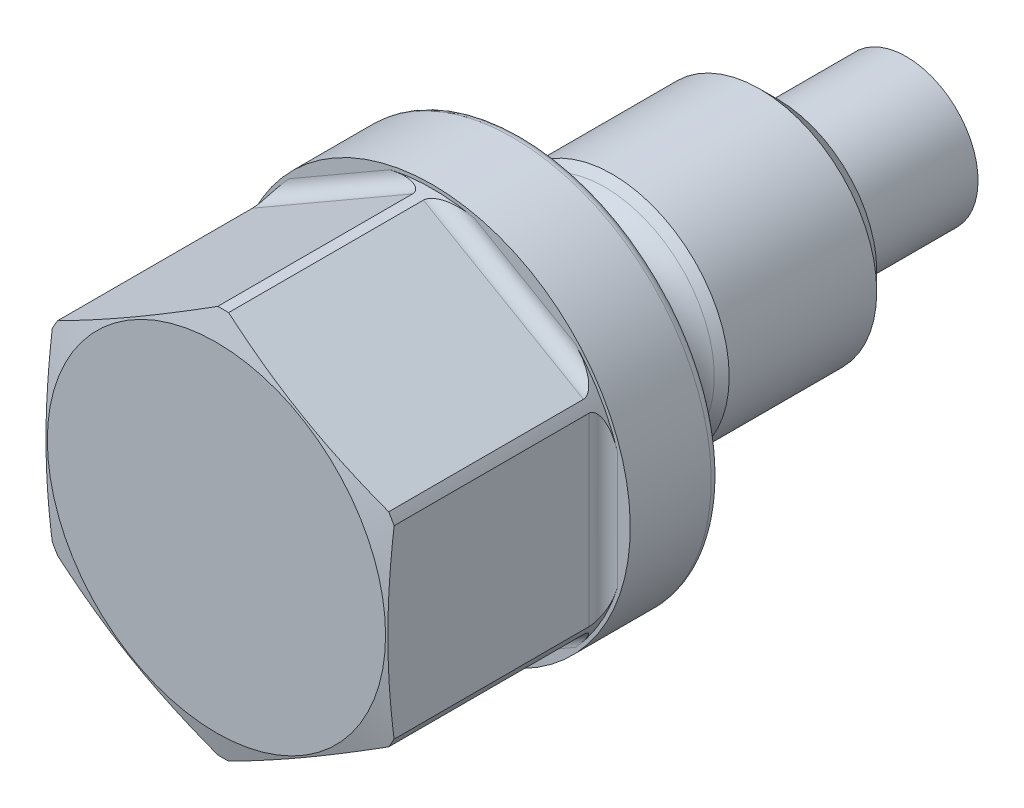
SolidWorks part; units mm, degrees
material "4140 H/T"
ref_plane "Front Plane" through (0, 0, 0) normal (0, 0, 1) x (1, 0, 0)
ref_plane "Top Plane" through (0, 0, 0) normal (0, 1, 0) x (1, 0, 0)
ref_plane "Right Plane" through (0, 0, 0) normal (1, 0, 0) x (0, 0, -1)
sketch "Sketch1" plane through (0, 0, 0) normal (1, 0, 0) x (0, 0, -1)
  line L0 (0, 0) -> (0, 2.85)
  line L1 (-0.6553, 3.985) -> (-7.4, 3.985)
  line L2 (-7.8, 4.385) -> (-7.8, 5.5)
  line L3 (-7.8, 5.5) -> (-8.8, 6.5)
  line L4 (-8.8, 6.5) -> (-17, 6.5)
  line L5 (-27, 10.8) -> (-27, 11)
  line L6 (-18.8284, 5.5) -> (-21.2, 5.5)
  line L7 (-22, 6.3) -> (-22, 10.5)
  line L8 (-22.5, 11) -> (-27, 11)
  line L9 (-39, 9.4) -> (-39, 0)
  line L10 (0, 0) -> (-39, 0) construction
  line L11 (0, 2.85) -> (-0.6553, 3.985)
  line L12 (0, 0) -> (-39, 0)
  line L13 (0, 0) -> (10.7751, 0) construction
  line L14 (-17.4142, 6.0858) -> (-17, 6.5)
  line L15 (-27, 10.8) -> (-38.6249, 10.8)
  line L16 (-39, 9.4) -> (-38.6249, 10.8)
  arc A0 (-21.2, 5.5) -> (-22, 6.3) centre (-21.2, 6.3) cw
  arc A1 (-17.4142, 6.0858) -> (-18.8284, 5.5) centre (-18.8284, 7.5) cw
  arc A2 (-22, 10.5) -> (-22.5, 11) centre (-22.5, 10.5) ccw
  arc A3 (-7.8, 4.385) -> (-7.4, 3.985) centre (-7.4, 4.385) ccw
  point P1 (0, 3.985)
  point P30 (-18, 5.5)
  dimension "D7" = 0.8
  dimension "D13" = 18.8
  dimension "D14" = 0.5
  dimension "D17" = 0.4
  dimension "D22" = 2
  dimension "D1" = 39
  dimension "D2" = 22
  dimension "D3" = 13
  dimension "D4" = 7.97
  dimension "D5" = 7.8
  dimension "D6" = 11
  dimension "D8" = 17
  dimension "D9" = 18
  dimension "D10" = 45
  dimension "D11" = 1
  dimension "D12" = 45
  dimension "D15" = 30
  dimension "D16" = 5.7
  dimension "D18" = 17
  dimension "D19" = 21.6
  dimension "D20" = 5
  dimension "D21" = 15
  dimension "D24" = 22
revolve "Revolve1" add sketch "Sketch1" angle 360 about L10
cosmetic thread "Cosmetic Thread1" parameters "D2"=11.43
sketch "Sketch2" plane through (0, 0, 39) normal (0, 0, 1) x (1, 0, 0)
  line L1 (0, -10.9697) -> (9.5, -5.4848)
  line L2 (9.5, -5.4848) -> (9.5, 5.4848)
  line L3 (9.5, 5.4848) -> (0, 10.9697)
  line L4 (0, 10.9697) -> (-9.5, 5.4848)
  line L5 (-9.5, 5.4848) -> (-9.5, -5.4848)
  line L6 (-9.5, -5.4848) -> (0, -10.9697)
  circle A0 centre (0, 0) radius 9.5 construction
  circle A1 centre (0, 0) radius 12.2582
  dimension "D2" = 24.5163
  dimension "D1" = 19
extrude "Cut-Extrude1" cut sketch "Sketch2" against normal up to surface (12 mm away) up to face at (0, 10.8, 27)
fillet "Fillet3" radius 0.8 2 edges at (-4.75, -8.2272, 27) (4.75, 8.2272, 27)
fillet "Fillet6" radius 0.8 2 edges at (-4.75, 8.2272, 27) (4.75, -8.2272, 27)
fillet "Fillet7" radius 0.8 2 edges at (9.5, 0, 27) (-9.5, 0, 27)
